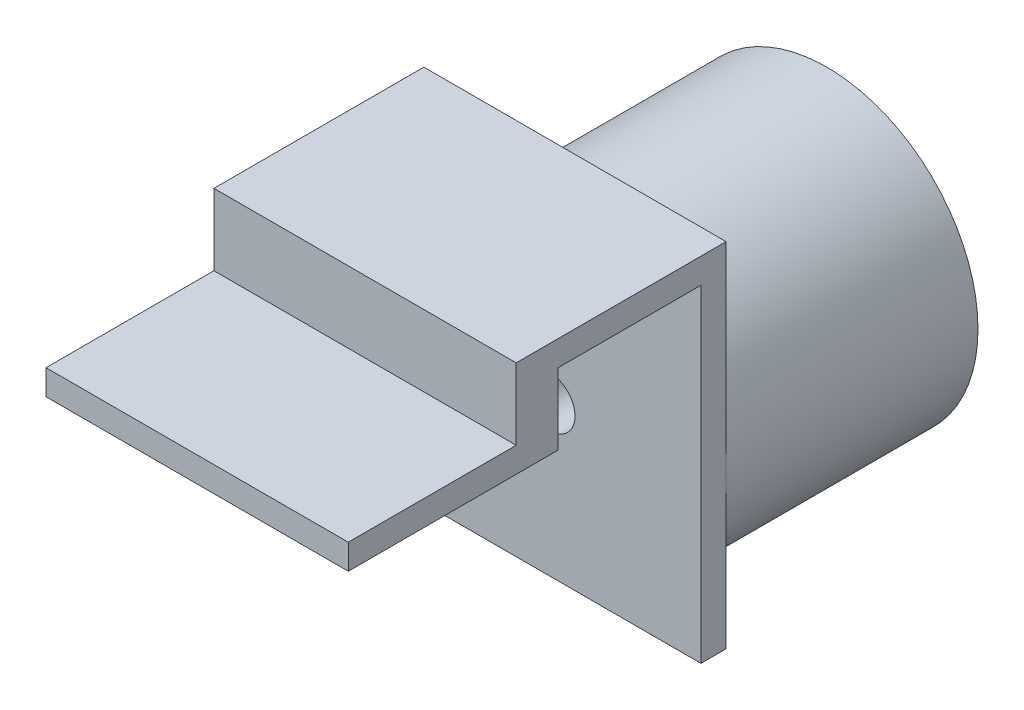
SolidWorks part; units mm, degrees
ref_plane "Front Plane" through (0, 0, 0) normal (0, 0, 1) x (1, 0, 0)
ref_plane "Top Plane" through (0, 0, 0) normal (0, 1, 0) x (1, 0, 0)
ref_plane "Right Plane" through (0, 0, 0) normal (1, 0, 0) x (0, 0, -1)
sketch "Sketch2" plane through (0, 0, 0) normal (0, 0, 1) x (1, 0, 0)
  circle A0 centre (0, 0) radius 18
extrude "Boss-Extrude1" add sketch "Sketch2" along normal blind 30
sketch "Sketch3" plane through (0, 0, 30) normal (0, 0, 1) x (1, 0, 0)
  circle A0 centre (0, 0) radius 3
  dimension "D1" = 0
sketch "Sketch4" plane through (0, 0, 30) normal (0, 0, 1) x (1, 0, 0)
  line L1 (-18, 24) -> (18, 24)
  line L2 (-18, 24) -> (-18, -18)
  line L3 (-18, -18) -> (18, -18)
  line L4 (18, 24) -> (18, -18)
  point P0 (0, 0)
  dimension "D1" = 36
  dimension "D2" = 42
  dimension "D3" = 18
extrude "Boss-Extrude2" add sketch "Sketch4" along normal blind 3
extrude "Cut-Extrude1" cut sketch "Sketch3" against normal blind 60 and the other way blind 3
sketch "Sketch6" plane through (0, 24, 0) normal (0, 1, 0) x (1, 0, 0)
  line L0 (-18, -33) -> (-18, -50)
  line L1 (-18, -50) -> (18, -50)
  line L2 (18, -50) -> (18, -33)
  line L3 (18, -33) -> (-18, -33)
  dimension "D1" = 17
extrude "Boss-Extrude3" add sketch "Sketch6" against normal blind 3
sketch "Sketch7" plane through (0, 0, 50) normal (0, 0, 1) x (1, 0, 0)
  line L1 (18, 21) -> (18, 12.5)
  line L2 (18, -18) -> (18, 21) construction
  line L3 (18, 12.5) -> (-18, 12.5)
  line L4 (-18, 21) -> (-18, -18) construction
  line L5 (-18, 12.5) -> (-18, 21)
  line L6 (-18, 24) -> (18, 24)
  line L7 (18, 24) -> (18, 21)
  line L8 (-18, 21) -> (-18, 24)
  dimension "D1" = 8.5
extrude "Boss-Extrude4" add sketch "Sketch7" along normal blind 5
sketch "Sketch8" plane through (0, 0, 55) normal (0, 0, 1) x (1, 0, 0)
  line L0 (-18, 12.5) -> (-18, 15.5)
  line L1 (-18, 24) -> (-18, 12.5) construction
  line L2 (-18, 15.5) -> (18, 15.5)
  line L3 (18, 12.5) -> (18, 24) construction
  line L4 (18, 15.5) -> (18, 12.5)
  line L5 (18, 12.5) -> (-18, 12.5)
  dimension "D1" = 3
extrude "Boss-Extrude5" add sketch "Sketch8" along normal blind 20
equation "\"7.5.00mm\"=20"
